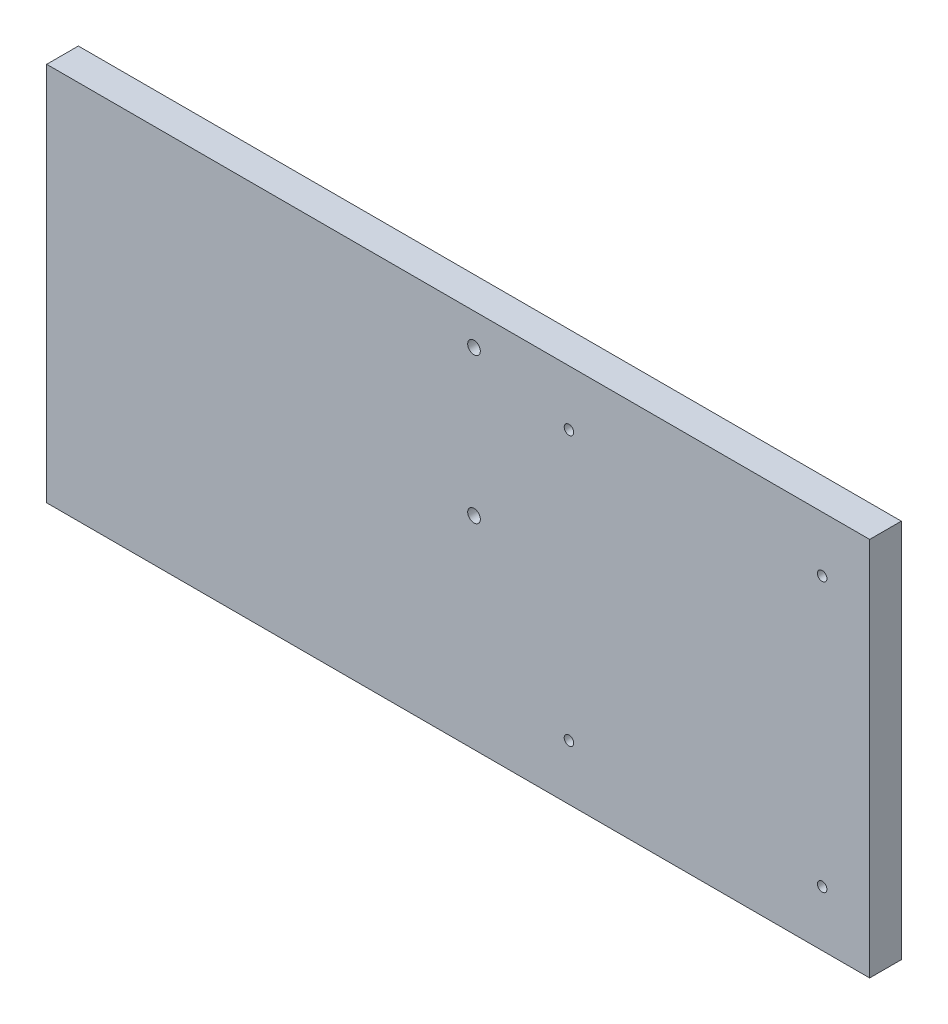
SolidWorks part; units mm, degrees
material "Faia"
ref_plane "Plano frontal" through (0, 0, 0) normal (0, 0, 1) x (1, 0, 0)
ref_plane "Plano superior" through (0, 0, 0) normal (0, 1, 0) x (1, 0, 0)
ref_plane "Plano direito" through (0, 0, 0) normal (1, 0, 0) x (0, 0, -1)
sketch "Esboço1" plane through (0, 0, 0) normal (0, 0, 1) x (1, 0, 0)
  line L0 (130, 0) -> (-130, 0) construction
  line L1 (-130, 60) -> (130, 60)
  line L2 (-130, 60) -> (-130, -60)
  line L3 (-130, -60) -> (130, -60)
  line L4 (130, 60) -> (130, -60)
  line L5 (-130, 60) -> (130, -60) construction
  line L6 (-130, -60) -> (130, 60) construction
  line L7 (50, 0) -> (-210, 0) construction
  line L8 (5, 4) -> (5, 50) construction
  circle A0 centre (115, 42.5) radius 1.5
  circle A1 centre (115, -42.5) radius 1.5
  circle A2 centre (35, -42.5) radius 1.5
  circle A3 centre (35, 42.5) radius 1.5
  circle A4 centre (5, 50) radius 2
  circle A5 centre (5, 4) radius 2
  point P0 (0, 0)
  point P21 (5, 0)
  dimension "D5" = 3
  dimension "D8" = 4
  dimension "D1" = 260
  dimension "D2" = 120
  dimension "D3" = 15
  dimension "D4" = 85
  dimension "D7" = 80
  dimension "D9" = 46
  dimension "D10" = 125
  dimension "D11" = 10
  dimension "D6" = 2
extrude "Ressalto-extrusão1" add sketch "Esboço1" along normal blind 10 contours L4 L1 L2 L3 A3 A1 A0 A2
